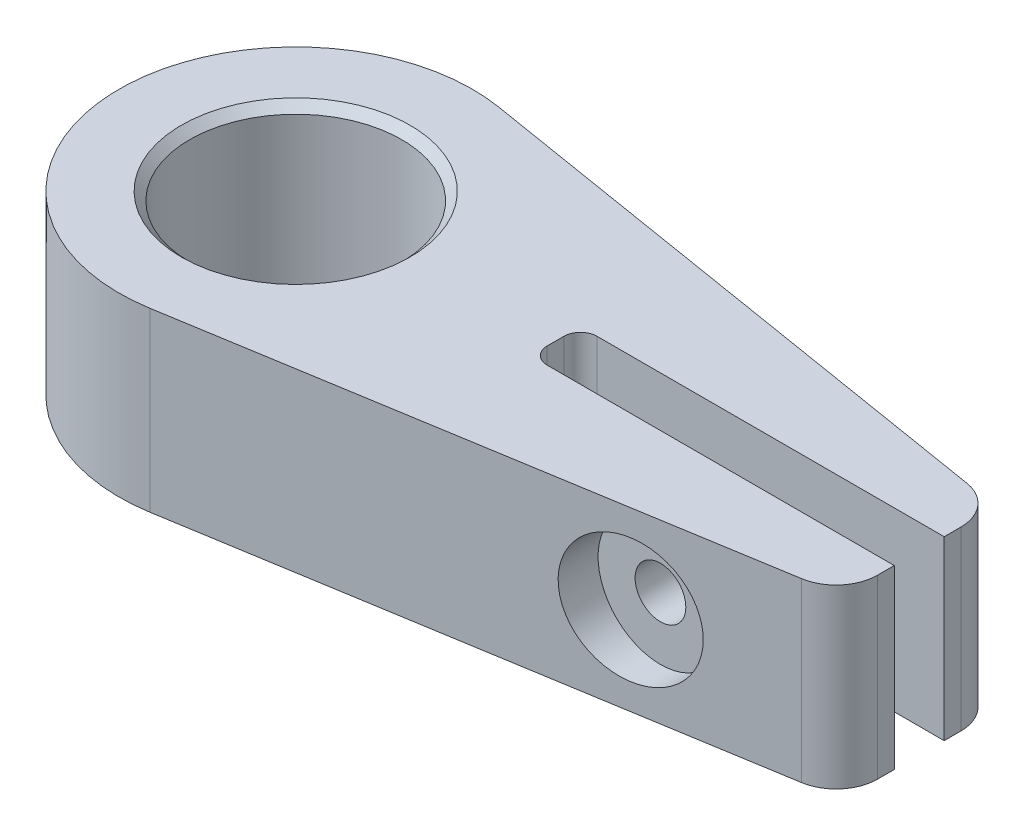
SolidWorks part; units mm, degrees
ref_plane "Front Plane" through (0, 0, 0) normal (0, 0, 1) x (1, 0, 0)
ref_plane "Top Plane" through (0, 0, 0) normal (0, 1, 0) x (1, 0, 0)
ref_plane "Right Plane" through (0, 0, 0) normal (1, 0, 0) x (0, 0, -1)
sketch "Sketch1" plane through (0, 0, 0) normal (0, 1, 0) x (1, 0, 0)
  line L0 (0, 0) -> (60.325, 0) construction
  line L1 (1.7444, 10.6531) -> (38.1, 4.7)
  line L2 (38.1, 4.7) -> (60.325, 4.7)
  line L3 (60.325, 4.7) -> (60.325, 1.525)
  line L4 (60.325, 1.525) -> (15.875, 1.525)
  line L5 (60.325, -1.525) -> (15.875, -1.525)
  line L6 (60.325, -4.7) -> (60.325, -1.525)
  line L7 (38.1, -4.7) -> (60.325, -4.7)
  line L8 (1.7444, -10.6531) -> (38.1, -4.7)
  line L9 (15.875, 1.525) -> (15.875, -1.525)
  circle A0 centre (0, 0) radius 6.477
  arc A1 (1.7444, 10.6531) -> (1.7444, -10.6531) centre (0, 0) ccw
  dimension "D1" = 12.954
  dimension "D2" = 21.59
  dimension "D3" = 60.325
  dimension "D4" = 3.05
  dimension "D5" = 3.175
  dimension "D6" = 38.1
  dimension "D7" = 15.875
extrude "Boss-Extrude1" add sketch "Sketch1" along normal blind 10.795
sketch "Sketch7" plane through (0, 10.795, 0) normal (0, 1, 0) x (1, 0, 0)
  circle A0 centre (0, -9.906) radius 1.5 construction
  circle A1 centre (0, 0) radius 6.477 construction
  circle A2 centre (0, -9.906) radius 1.9685
  dimension "D2" = 3
  dimension "D3" = 3.937
  dimension "D1" = 9.906
extrude "Cut-Extrude2" [suppressed] cut sketch "Sketch7" against normal through all
sketch "Sketch8" plane through (0, 0, 4.7) normal (0, 0, 1) x (1, 0, 0)
  line L0 (60.325, 5.3975) -> (15.875, 5.3975) construction
  line L1 (60.325, 10.795) -> (60.325, 0) construction
  line L2 (15.875, 10.795) -> (15.875, 0) construction
  line L3 (15.875, 10.795) -> (15.875, 0) construction
  line L4 (38.1, 10.795) -> (38.1, 0) construction
  line L5 (38.1, 10.795) -> (60.325, 10.795) construction
  line L6 (38.1, 0) -> (60.325, 0) construction
  line L7 (26.9875, 5.3975) -> (26.9875, 10.795) construction
  line L8 (1.7444, 10.795) -> (38.1, 10.795) construction
  line L9 (15.875, 0) -> (38.1, 0) construction
  circle A0 centre (26.9875, 5.3975) radius 1.55
  circle A1 centre (49.2125, 5.3975) radius 1.55
  point P1 (38.1, 5.3975)
  point P17 (26.9875, 0)
  dimension "D1" = 3.1
extrude "Cut-Extrude3" cut sketch "Sketch8" against normal through all both and the other way through all
sketch "Sketch9" plane through (0, 0, 4.7) normal (0, 0, 1) x (1, 0, 0)
  circle A0 centre (26.9875, 5.3975) radius 3.81
  dimension "D1" = 7.62
extrude "Cut-Extrude4" cut sketch "Sketch9" along normal through all
sketch "Sketch10" plane through (0, 0, -4.7) normal (0, 0, -1) x (-1, 0, 0)
  line L1 (-24.13, 3.7477) -> (-24.13, 7.0473)
  line L2 (-24.13, 7.0473) -> (-26.9875, 8.6971)
  line L3 (-26.9875, 8.6971) -> (-29.845, 7.0473)
  line L4 (-29.845, 7.0473) -> (-29.845, 3.7477)
  line L5 (-29.845, 3.7477) -> (-26.9875, 2.0979)
  line L6 (-26.9875, 2.0979) -> (-24.13, 3.7477)
  circle A0 centre (-26.9875, 5.3975) radius 2.8575 construction
  dimension "D1" = 5.715
extrude "Cut-Extrude5" cut sketch "Sketch10" along normal through all
fillet "Fillet1" radius 1.016 2 edges at (15.875, 5.3975, -1.525) (15.875, 5.3975, 1.525)
sketch "Sketch11" plane through (0, 10.795, 0) normal (0, 1, 0) x (1, 0, 0)
  line L0 (15.875, -0.509) -> (15.875, 0.509) construction
  line L1 (15.875, -1.525) -> (60.325, -1.525)
  line L2 (15.875, -1.525) -> (15.875, 1.525)
  line L3 (15.875, 1.525) -> (60.325, 1.525)
  line L4 (60.325, -1.525) -> (60.325, 1.525)
  line L5 (60.325, -1.525) -> (16.891, -1.525) construction
extrude "Boss-Extrude5" [suppressed] add sketch "Sketch11" against normal blind 3.175
sketch "Sketch12" [suppressed] plane through (0, 16.764, 0) normal (0, 1, 0) x (1, 0, 0)
  line L0 (0, 0) -> (60.325, 0) construction
  line L1 (60.325, -4.7) -> (60.325, 4.7) construction
  line L3 (38.1, -12.7) -> (38.1, -4.7) construction
  line L4 (31.9646, -12.7) -> (31.9646, -1.525)
  line L5 (31.9646, -1.525) -> (44.2354, -1.525)
  line L6 (44.2354, -1.525) -> (44.2354, -12.7)
  line L7 (16.891, -1.525) -> (60.325, -1.525) construction
  line L8 (16.891, -1.525) -> (60.325, -1.525) construction
  circle A0 centre (38.1, -12.7) radius 2.413
  arc A1 (31.9646, -12.7) -> (44.2354, -12.7) centre (38.1, -12.7) ccw
  dimension "D1" = 4.826
  dimension "D2" = 12.7
extrude "Boss-Extrude6" [suppressed] add sketch "Sketch12" against normal blind 8.89
sketch "Sketch13" plane through (0, 0, 0) normal (0, -1, 0) x (1, 0, 0)
  line L1 (60.325, 4.7) -> (38.1, 4.7)
  line L2 (60.325, 4.7) -> (60.325, -4.7)
  line L3 (60.325, -4.7) -> (38.1, -4.7)
  line L4 (38.1, 4.7) -> (38.1, -4.7)
extrude "Cut-Extrude6" cut sketch "Sketch13" against normal through all
fillet "Fillet2" [suppressed] radius 1.016
fillet "Fillet3" [suppressed] radius 2.54
fillet "Fillet4" [suppressed] radius 0.762
fillet "Fillet5" [suppressed] radius 6.35
fillet "Fillet6" [suppressed] radius 1.27
fillet "Fillet7" radius 2.54 2 edges at (38.1, 5.3975, -4.7) (38.1, 5.3975, 4.7)
chamfer "Chamfer1" [suppressed] distance 0.508 angle 45
chamfer "Chamfer2" distance 0.508 angle 45 2 edges at (0, 10.795, 6.477) (0, 0, 6.477)
